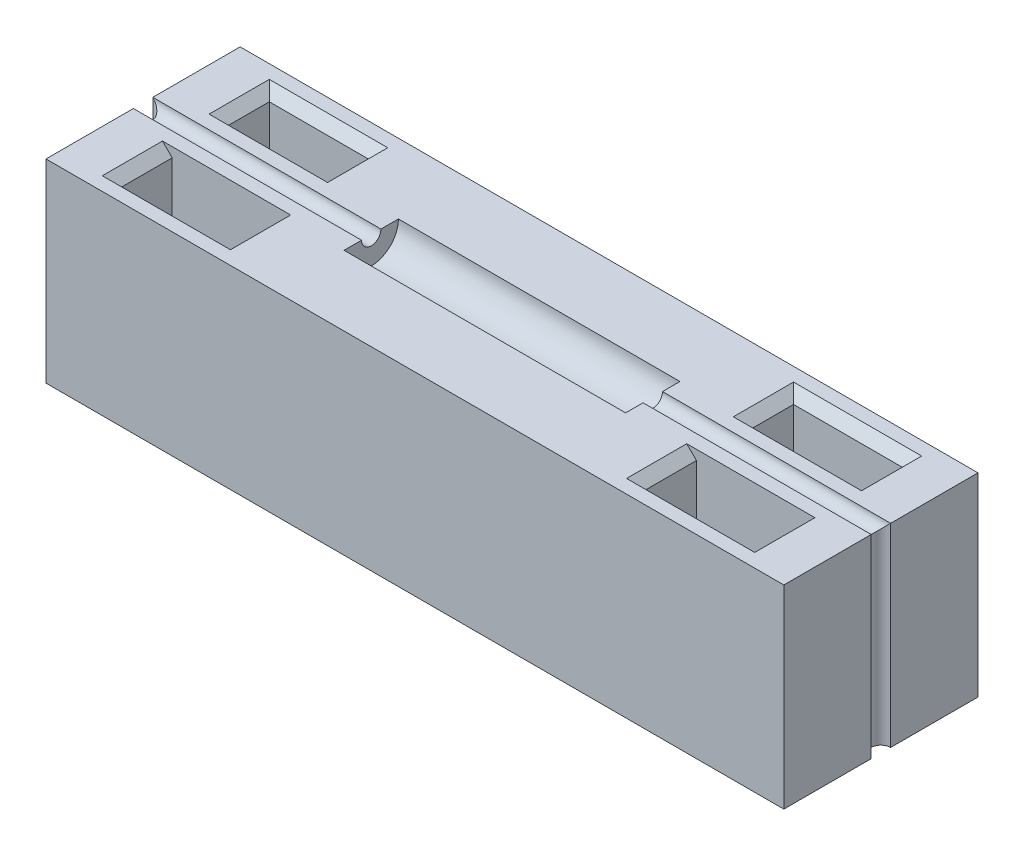
SolidWorks part; units mm, degrees
ref_plane "Front Plane" through (0, 0, 0) normal (0, 0, 1) x (1, 0, 0)
ref_plane "Top Plane" through (0, 0, 0) normal (0, 1, 0) x (1, 0, 0)
ref_plane "Right Plane" through (0, 0, 0) normal (1, 0, 0) x (0, 0, -1)
sketch "Sketch1" plane through (0, 0, 0) normal (0, 1, 0) x (1, 0, 0)
  line L1 (0, 0) -> (38, 0)
  line L2 (0, 0) -> (0, 10)
  line L3 (0, 10) -> (38, 10)
  line L4 (38, 0) -> (38, 10)
  dimension "D1" = 10
  dimension "D2" = 38
extrude "Boss-Extrude1" add sketch "Sketch1" along normal blind 10
sketch "Sketch2" plane through (0, 10, 0) normal (0, 1, 0) x (1, 0, 0)
  line L0 (0, 5) -> (38, 5)
  line L1 (0, 10) -> (0, 0) construction
  line L2 (38, 0) -> (38, 10) construction
  line L3 (0, 4.5) -> (11.75, 4.5)
  line L4 (11.75, 4.5) -> (11.75, 3.6)
  line L5 (11.75, 3.6) -> (26.25, 3.6)
  line L6 (26.25, 3.6) -> (26.25, 4.5)
  line L7 (26.25, 4.5) -> (38, 4.5)
  line L8 (0, 4.5) -> (0, 5)
  line L9 (38, 4.5) -> (38, 5)
  line L10 (19, 10) -> (19, 0) construction
  line L11 (38, 10) -> (0, 10) construction
  line L12 (0, 0) -> (38, 0) construction
  dimension "D1" = 14.5
  dimension "D2" = 0.5
  dimension "D3" = 1.4
revolve "Cut-Revolve1" cut sketch "Sketch2" angle 360 about L0
sketch "Sketch3" plane through (0, 10, 0) normal (0, 1, 0) x (1, 0, 0)
  line L0 (0, 5) -> (38, 5) construction
  line L1 (0, 5) -> (38, 5) construction
  line L2 (0, 5.5) -> (0, 4.5) construction
  line L3 (38, 4.5) -> (38, 5.5) construction
  line L4 (19, 10) -> (19, 0) construction
  line L5 (38, 10) -> (0, 10) construction
  line L6 (0, 0) -> (38, 0) construction
  circle A0 centre (0, 5) radius 0.5
  circle A1 centre (38, 5) radius 0.5
  dimension "D2" = 1
  dimension "D1" = 38
extrude "Cut-Extrude1" cut sketch "Sketch3" against normal through all
sketch "Sketch4" plane through (0, 10, 0) normal (0, 1, 0) x (1, 0, 0)
  line L0 (0, 10) -> (0, 5.5) construction
  line L1 (3, 8.5) -> (8, 8.5) construction
  line L2 (3, 8.5) -> (3, 6.5) construction
  line L3 (3, 6.5) -> (8, 6.5) construction
  line L4 (8, 8.5) -> (8, 6.5) construction
  line L5 (30, 8.5) -> (35, 8.5) construction
  line L6 (30, 8.5) -> (30, 6.5) construction
  line L7 (30, 6.5) -> (35, 6.5) construction
  line L8 (35, 8.5) -> (35, 6.5) construction
  line L9 (30, 3.5) -> (35, 3.5) construction
  line L10 (30, 3.5) -> (30, 1.5) construction
  line L11 (30, 1.5) -> (35, 1.5) construction
  line L12 (35, 3.5) -> (35, 1.5) construction
  line L13 (3, 3.5) -> (8, 3.5) construction
  line L14 (3, 3.5) -> (3, 1.5) construction
  line L15 (3, 1.5) -> (8, 1.5) construction
  line L16 (8, 3.5) -> (8, 1.5) construction
  line L18 (38, 10) -> (0, 10) construction
  line L19 (0, 0) -> (38, 0) construction
  line L20 (38, 5.5) -> (38, 10) construction
  line L21 (2.7, 6.2) -> (8.3, 6.2)
  line L22 (8.3, 8.8) -> (8.3, 6.2)
  line L23 (2.7, 8.8) -> (8.3, 8.8)
  line L24 (2.7, 8.8) -> (2.7, 6.2)
  line L25 (2.7, 3.8) -> (2.7, 1.2)
  line L26 (2.7, 1.2) -> (8.3, 1.2)
  line L27 (8.3, 3.8) -> (8.3, 1.2)
  line L28 (2.7, 3.8) -> (8.3, 3.8)
  line L29 (29.7, 8.8) -> (35.3, 8.8)
  line L30 (35.3, 8.8) -> (35.3, 6.2)
  line L31 (29.7, 6.2) -> (35.3, 6.2)
  line L32 (29.7, 8.8) -> (29.7, 6.2)
  line L33 (29.7, 1.2) -> (35.3, 1.2)
  line L34 (35.3, 3.8) -> (35.3, 1.2)
  line L35 (29.7, 3.8) -> (35.3, 3.8)
  line L36 (29.7, 3.8) -> (29.7, 1.2)
  point P40 (0, 0)
  dimension "D1" = 3
  dimension "D2" = 2
  dimension "D3" = 5
  dimension "D4" = 1.5
  dimension "D5" = 1.5
  dimension "D6" = 3
  dimension "D7" = 0.3
extrude "Cut-Extrude2" cut sketch "Sketch4" against normal blind 4.2
chamfer "Chamfer1" distance 0.5 angle 45 11 edges at (35.3, 10, -2.5) (32.5, 10, -1.2) (29.7, 10, -2.5) (35.3, 10, -7.5) (29.7, 10, -7.5) (32.5, 10, -8.8) (8.3, 10, -2.5) (5.5, 10, -1.2) (2.7, 10, -2.5) (2.7, 10, -7.5) (5.5, 10, -8.8)
